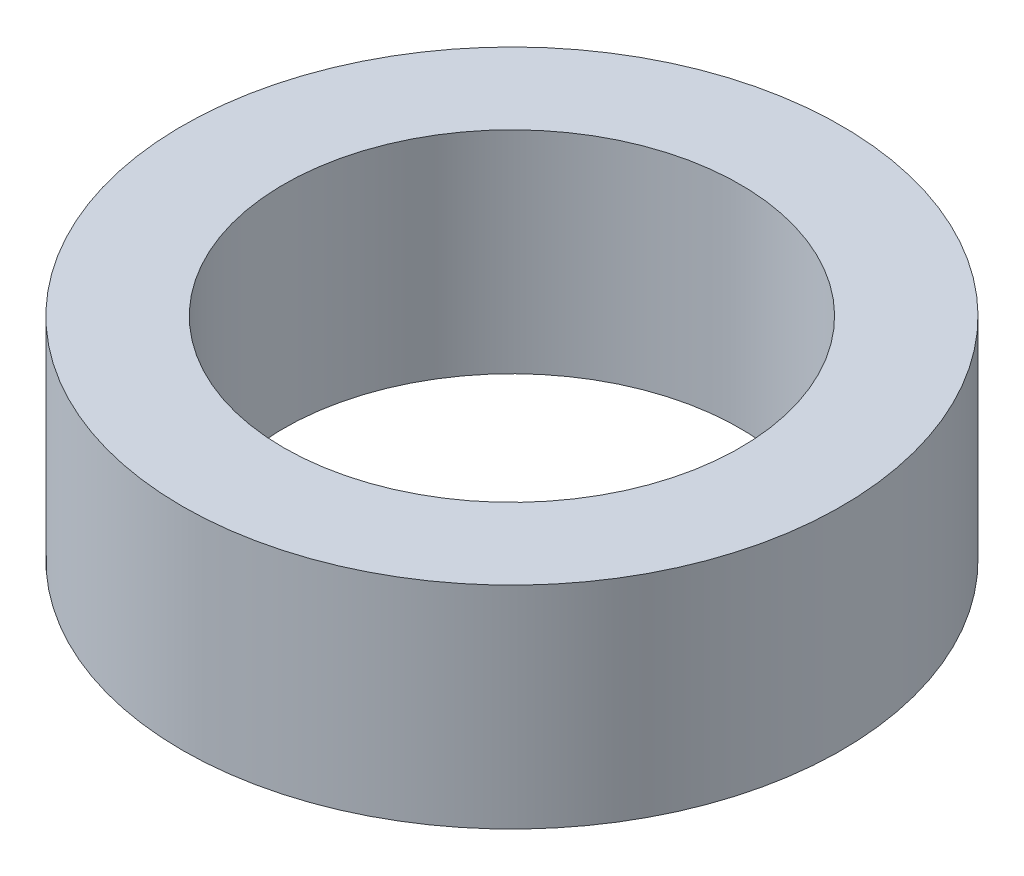
SolidWorks part; units mm, degrees
material "橡胶"
ref_plane "前视基准面" through (0, 0, 0) normal (0, 0, 1) x (1, 0, 0)
ref_plane "上视基准面" through (0, 0, 0) normal (0, 1, 0) x (1, 0, 0)
ref_plane "右视基准面" through (0, 0, 0) normal (1, 0, 0) x (0, 0, -1)
other "Configuration Table"
sketch "草图1" plane through (0, 0, 0) normal (0, 1, 0) x (1, 0, 0)
  circle A0 centre (0, 0) radius 31.2
  circle A1 centre (0, 0) radius 21.6
  dimension "D1" = 43.2
  dimension "D2" = 62.4
extrude "凸台-拉伸1" add sketch "草图1" along normal blind 20
